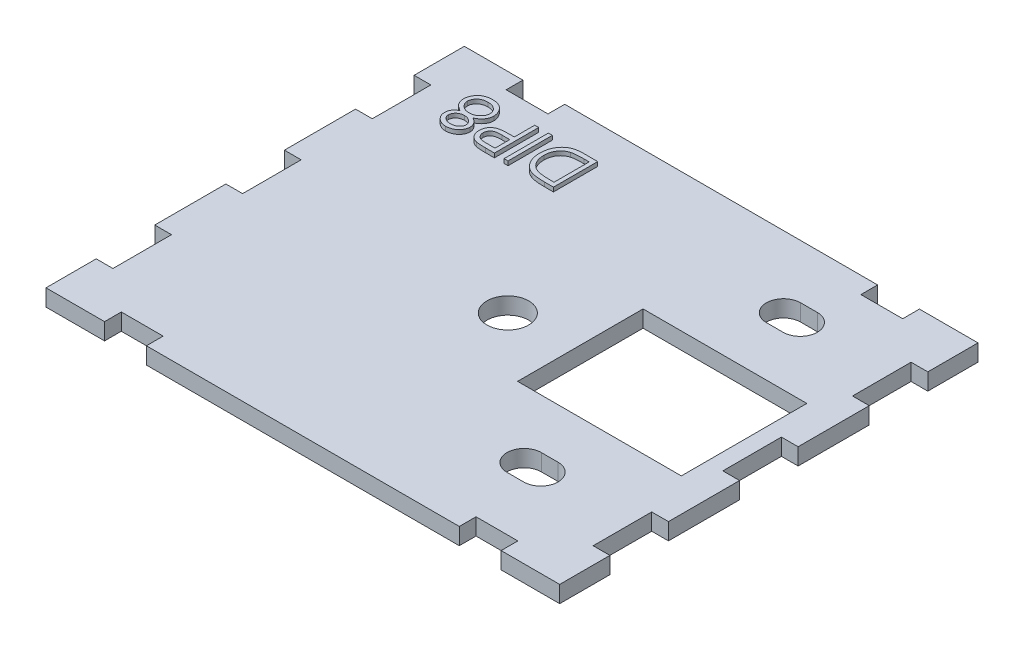
SolidWorks part; units mm, degrees
ref_plane "Front Plane" through (0, 0, 0) normal (0, 0, 1) x (1, 0, 0)
ref_plane "Top Plane" through (0, 0, 0) normal (0, 1, 0) x (1, 0, 0)
ref_plane "Right Plane" through (0, 0, 0) normal (1, 0, 0) x (0, 0, -1)
sketch "Sketch2" plane through (0, 0, 0) normal (0, 1, 0) x (1, 0, 0)
  line L1 (-50, 25) -> (50, 25)
  line L2 (-50, 25) -> (-50, -25)
  line L3 (-50, -25) -> (50, -25)
  line L4 (50, 25) -> (50, -25)
  line L5 (-50, 25) -> (50, -25) construction
  line L6 (-50, -25) -> (50, 25) construction
  point P0 (0, 0)
  dimension "D1" = 100
  dimension "D2" = 50
extrude "Boss-Extrude1" add sketch "Sketch2" along normal blind 2
sketch "Sketch12" plane through (0, 2, 0) normal (0, 1, 0) x (1, 0, 0)
  line L0 (-50, -25) -> (50, -25) construction
  line L1 (-40.2, -25) -> (-50, -25)
  line L2 (-40.2, -25) -> (-40.2, 25)
  line L3 (-40.2, 25) -> (-50, 25)
  line L4 (-50, -25) -> (-50, 25)
  line L5 (-50, -25) -> (50, -25) construction
  line L6 (41.2, -25) -> (50, -25)
  line L7 (41.2, -25) -> (41.2, 25)
  line L8 (41.2, 25) -> (50, 25)
  line L9 (50, -25) -> (50, 25)
extrude "Cut-Extrude8" cut sketch "Sketch12" against normal blind 6
sketch "Sketch13" plane through (0, 2, 0) normal (0, 1, 0) x (1, 0, 0)
  line L1 (-28.2, 19) -> (-30.2, 19)
  line L2 (-28.2, 19) -> (-28.2, 12)
  line L3 (-28.2, 12) -> (-30.2, 12)
  line L4 (-30.2, 19) -> (-30.2, 12)
  line L5 (-28.2, 3.5) -> (-30.2, 3.5)
  line L6 (-28.2, 3.5) -> (-28.2, -3.5)
  line L7 (-28.2, -3.5) -> (-30.2, -3.5)
  line L8 (-30.2, 3.5) -> (-30.2, -3.5)
  line L9 (-28.2, -12) -> (-30.2, -12)
  line L10 (-28.2, -12) -> (-28.2, -19)
  line L11 (-28.2, -19) -> (-30.2, -19)
  line L12 (-30.2, -12) -> (-30.2, -19)
  line L13 (29.2, 19) -> (31.2, 19)
  line L14 (29.2, 19) -> (29.2, 12)
  line L15 (29.2, 12) -> (31.2, 12)
  line L16 (31.2, 19) -> (31.2, 12)
  line L17 (29.2, 3.5) -> (31.2, 3.5)
  line L18 (29.2, 3.5) -> (29.2, -3.5)
  line L19 (29.2, -3.5) -> (31.2, -3.5)
  line L20 (31.2, 3.5) -> (31.2, -3.5)
  line L21 (29.2, -12) -> (31.2, -12)
  line L22 (29.2, -12) -> (29.2, -19)
  line L23 (29.2, -19) -> (31.2, -19)
  line L24 (31.2, -12) -> (31.2, -19)
  line L25 (-40.2, -25) -> (41.2, -25) construction
  line L26 (-23.2, 25) -> (-18.2, 25)
  line L27 (41.2, 25) -> (-40.2, 25) construction
  line L28 (-40.2, -25) -> (41.2, -25) construction
  line L29 (41.2, 25) -> (-40.2, 25) construction
  line L30 (-40.2, -25) -> (41.2, -25) construction
  line L31 (41.2, 25) -> (31.2, 25)
  line L32 (41.2, 25) -> (41.2, -25)
  line L33 (41.2, -25) -> (31.2, -25)
  line L34 (31.2, 25) -> (31.2, -25)
  line L35 (41.2, 25) -> (-40.2, 25) construction
  line L36 (-40.2, -25) -> (-30.2, -25)
  line L37 (-40.2, -25) -> (-40.2, 25)
  line L38 (-40.2, 25) -> (-30.2, 25)
  line L39 (-30.2, -25) -> (-30.2, 25)
  line L40 (-23.2, 25) -> (-23.2, 23)
  line L41 (-23.2, 23) -> (-18.2, 23)
  line L42 (-18.2, 25) -> (-18.2, 23)
  line L43 (-23.2, -25) -> (-18.2, -25)
  line L44 (-23.2, -25) -> (-23.2, -23)
  line L45 (-23.2, -23) -> (-18.2, -23)
  line L46 (-18.2, -25) -> (-18.2, -23)
  line L47 (24.2, -25) -> (19.2, -25)
  line L48 (24.2, -25) -> (24.2, -23)
  line L49 (24.2, -23) -> (19.2, -23)
  line L50 (19.2, -25) -> (19.2, -23)
  line L51 (24.2, 25) -> (19.2, 25)
  line L52 (24.2, 25) -> (24.2, 23)
  line L53 (24.2, 23) -> (19.2, 23)
  line L54 (19.2, 25) -> (19.2, 23)
  point P24 (29.2, 0)
  point P30 (30.2, 3.5)
  line M32 (41.2, -25) -> (41.2, 25)
  line M41 (41.2, 25) -> (-40.2, 25)
  line M42 (-40.2, 25) -> (-40.2, -25)
  line M47 (-40.2, -25) -> (41.2, -25)
  dimension "D1" = 2
  dimension "D2" = 2
  dimension "D3" = 2
  dimension "D4" = 2
  dimension "D5" = 2
  dimension "D6" = 2
  dimension "D7" = 57.4
  dimension "D8" = 57.4
  dimension "D9" = 57.4
  dimension "D10" = 7
  dimension "D11" = 7
  dimension "D12" = 7
  dimension "D13" = 7
  dimension "D14" = 7
  dimension "D15" = 7
  dimension "D16" = 5
  dimension "D17" = 2
  dimension "D18" = 5
  dimension "D19" = 6
  dimension "D20" = 8.5
  dimension "D21" = 8.5
  dimension "D22" = 6
  dimension "D23" = 6
  dimension "D24" = 8.5
  dimension "D25" = 8.5
  dimension "D26" = 6
  dimension "D27" = 5
  dimension "D28" = 5
  dimension "D29" = 2
  dimension "D30" = 2
  dimension "D31" = 5
  dimension "D32" = 5
  dimension "D33" = 5
  dimension "D34" = 5
  dimension "D35" = 2
extrude "Cut-Extrude10" cut sketch "Sketch13" against normal blind 6 contours L5 L8 L7 L6 | L39 L12 L8 L4 M47 M41 M42 | L1 L4 L3 L2 | L50 L48 L49 M47 | L24 L21 L22 L23 | L20 L17 L18 L19 | L16 L13 L14 L15 | L54 L53 L52 M41 | L9 L12 L11 L10 | L34 L16 L20 L24 M41 M47 M32 | L26 L42 L41 L40 | L45 L46 L43 L44
sketch "Sketch15" plane through (0, 0, 0) normal (0, -1, 0) x (1, 0, 0)
  line L0 (24.2, 23) -> (19.2, 23) construction
  line L1 (31.2, -12) -> (31.2, -3.5) construction
  line L16 (20.7242, -7.5) -> (20.7242, -8.5)
  line L17 (20.7242, -7.5) -> (25.936, -7.5)
  line L18 (25.936, -7.5) -> (25.936, 5.5)
  line L19 (25.936, 5.5) -> (8.9693, 5.5)
  line L20 (8.9693, 5.5) -> (8.9693, -7.5)
  line L21 (8.9693, -7.5) -> (14.1811, -7.5)
  line L22 (14.1811, -7.5) -> (14.1811, -8.5)
  line L23 (14.1811, -8.5) -> (7.6661, -8.5)
  line L24 (7.6661, -8.5) -> (7.6661, 6.5)
  line L25 (7.6661, 6.5) -> (27.2392, 6.5)
  line L26 (27.2392, 6.5) -> (27.2392, -8.5)
  line L27 (27.2392, -8.5) -> (20.7242, -8.5)
  line L28 (20.7242, -8.5) -> (14.1811, -8.5)
  line L29 (14.1811, -7.5) -> (20.7242, -7.5)
  dimension "D1" = 13
  dimension "D4" = 16.5
  dimension "D5" = 6.5431
  dimension "D6" = 90
  dimension "D7" = 3.9608
  dimension "D8" = 90
  dimension "D9" = 1.3032
  dimension "D24" = 5.2118
  dimension "D25" = 5.2118
  dimension "D26" = 6.515
  dimension "D27" = 6.515
  dimension "D28" = 1
  dimension "D31" = 90
  dimension "D32" = 90
  dimension "D34" = 1
extrude "Cut-Extrude13" cut sketch "Sketch15" against normal blind 10 contours L21 L29 L17 L18 L19 L20 | L27 L26 L25 L24 L23 L22 L21 L20 L19 L18 L17 L16 | L29 L22 L28 L16
sketch "Sketch16" plane through (0, 0, 0) normal (0, -1, 0) x (-1, 0, 0)
  circle A0 centre (0, 0) radius 2.5
  dimension "D1" = 5
extrude "Cut-Extrude14" cut sketch "Sketch16" against normal blind 10 contours A0
sketch "Sketch17" plane through (0, 0, 0) normal (0, -1, 0) x (-1, 0, 0)
  line L0 (-16.4527, 18.55) -> (-18.4527, 18.55)
  line L1 (-16.4527, 14.45) -> (-18.4527, 14.45)
  line L2 (-27.2392, 8.5) -> (-7.6661, 8.5) construction
  line L3 (-16.4527, -12.45) -> (-18.4527, -12.45)
  line L4 (-7.6661, -6.5) -> (-27.2392, -6.5) construction
  line L5 (-18.4527, -16.55) -> (-16.4527, -16.55)
  circle A0 centre (-17.4527, -14.5) radius 2.05
  circle A1 centre (-17.4527, 16.5) radius 2.05
  circle A2 centre (-16.4527, 16.5) radius 2.05
  circle A3 centre (-18.4527, 16.5) radius 2.05
  circle A4 centre (-18.4527, -14.5) radius 2.05
  circle A5 centre (-16.4527, -14.5) radius 2.05
  dimension "D1" = 4.1
  dimension "D2" = 4.1
  dimension "D9" = 1
  dimension "D10" = 0
  dimension "D12" = 0
  dimension "D15" = 0
  dimension "D16" = 0
  dimension "D3" = 8
  dimension "D4" = 9.7866
  dimension "D5" = 9.7866
  dimension "D6" = 9.7866
  dimension "D7" = 9.7866
  dimension "D8" = 8
  dimension "D11" = 1
  dimension "D13" = 1
  dimension "D14" = 1
extrude "Cut-Extrude15" cut sketch "Sketch17" against normal blind 3.5 contours A4 A0 | A5 A4 A0 | A4 A5 | A0 A5 A4 | A5 A0 | A5 L3 A0 | A5 A0 A4 | A4 A0 L3 | A5 A0 L5 | A5 A4 A0 | A4 L5 A0 | A2 A3 | A1 A3 A2 | A3 A1 | A3 A2 A1 | A3 A1 A2 | A3 A2 A1 | A2 A1 | A2 A1 L1 | A3 L1 A1 | A3 A1 L0 | A2 L0 A1
sketch "Sketch22" plane through (0, 2, 0) normal (0, 1, 0) x (1, 0, 0)
  line L0 (-24.5837, 20.5398) -> (4.8961, 20.5398) construction
  text T0 "DIP8" font "Century Gothic" height in points 20
extrude "Boss-Extrude4" add sketch "Sketch22" along normal blind 0.5
